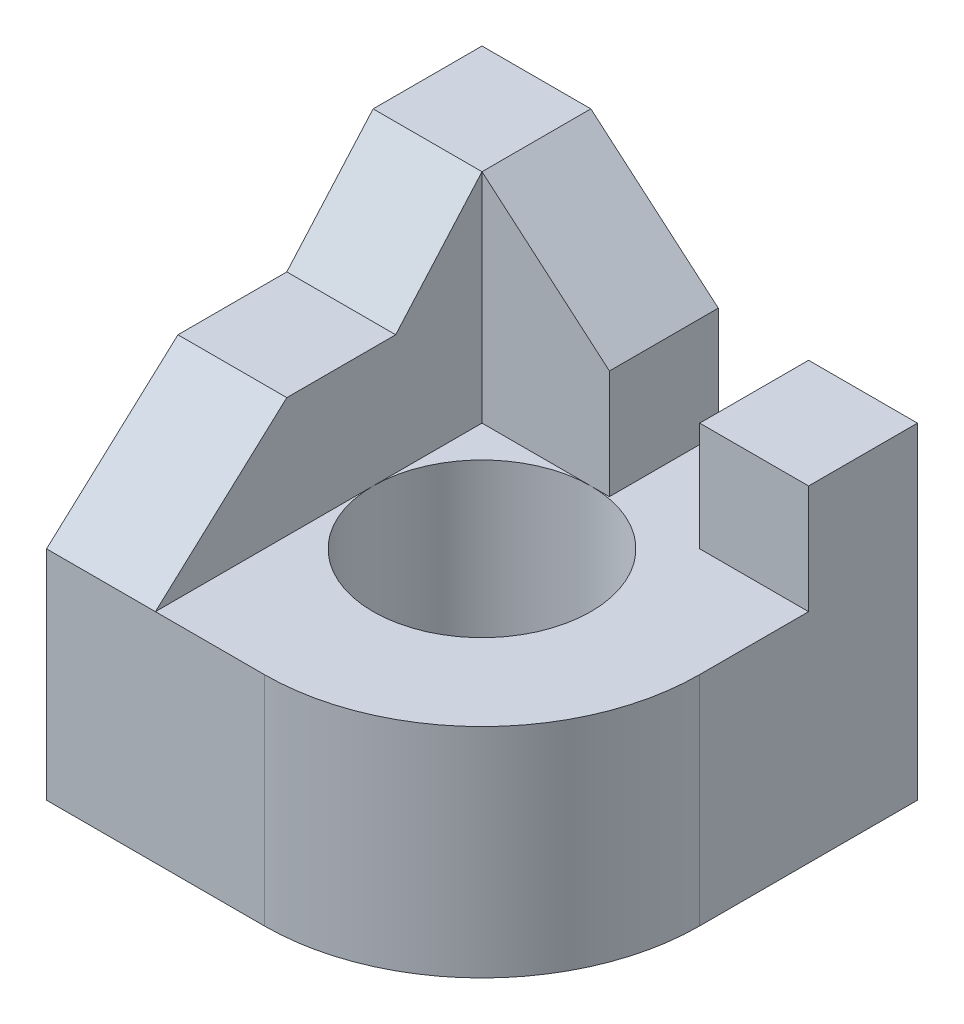
SolidWorks part; units mm, degrees
ref_plane "前基準面" through (0, 0, 0) normal (0, 0, 1) x (1, 0, 0)
ref_plane "上基準面" through (0, 0, 0) normal (0, 1, 0) x (1, 0, 0)
ref_plane "右基準面" through (0, 0, 0) normal (1, 0, 0) x (0, 0, -1)
sketch "草圖1" plane through (0, 0, 0) normal (0, 1, 0) x (1, 0, 0)
  line L0 (0, 0) -> (4, 0)
  line L1 (4, 0) -> (4, -2)
  line L2 (0, 0) -> (0, -4)
  line L3 (0, -4) -> (2, -4)
  arc A0 (4, -2) -> (2, -4) centre (2, -2) cw
  dimension "D3" = 2
  dimension "D1" = 4
  dimension "D2" = 4
extrude "填料-伸長1" add sketch "草圖1" along normal blind 2
sketch "草圖2" plane through (0, 0, 0) normal (0, 0, -1) x (-1, 0, 0)
  line L0 (-4, 2) -> (-4, 3)
  line L1 (-4, 3) -> (-3, 3)
  line L2 (-3, 3) -> (-3, 2)
  line L3 (-4, 2) -> (0, 2) construction
  line L4 (-3, 2) -> (-4, 2)
  line L5 (0, 2) -> (0, 4)
  line L8 (-1.4869, 2) -> (0, 2)
  line L9 (0, 4) -> (-1, 4)
  line L10 (-1, 4) -> (-2.1706, 3)
  line L11 (-2.1706, 3) -> (-2.1706, 2)
  line L12 (-2.1706, 2) -> (-1.4869, 2)
  dimension "D1" = 1
  dimension "D2" = 1
  dimension "D3" = 2
  dimension "D4" = 1
  dimension "D5" = 1
extrude "填料-伸長2" add sketch "草圖2" against normal blind 1
sketch "草圖3" plane through (0, 0, 0) normal (-1, 0, 0) x (0, 0, 1)
  line L0 (1, 4) -> (1.793, 3.0993)
  line L1 (1.793, 3.0993) -> (2.793, 3.0993)
  line L2 (2.793, 3.0993) -> (4, 2)
  line L3 (4, 2) -> (1, 2)
  line L4 (1, 2) -> (1, 4)
  dimension "D1" = 1
extrude "填料-伸長3" add sketch "草圖3" against normal blind 1
sketch "草圖4" plane through (0, 2, 0) normal (0, 1, 0) x (1, 0, 0)
  circle A0 centre (2, -2) radius 1
  dimension "D1" = 2
extrude "除料-伸長1" cut sketch "草圖4" against normal blind 3
